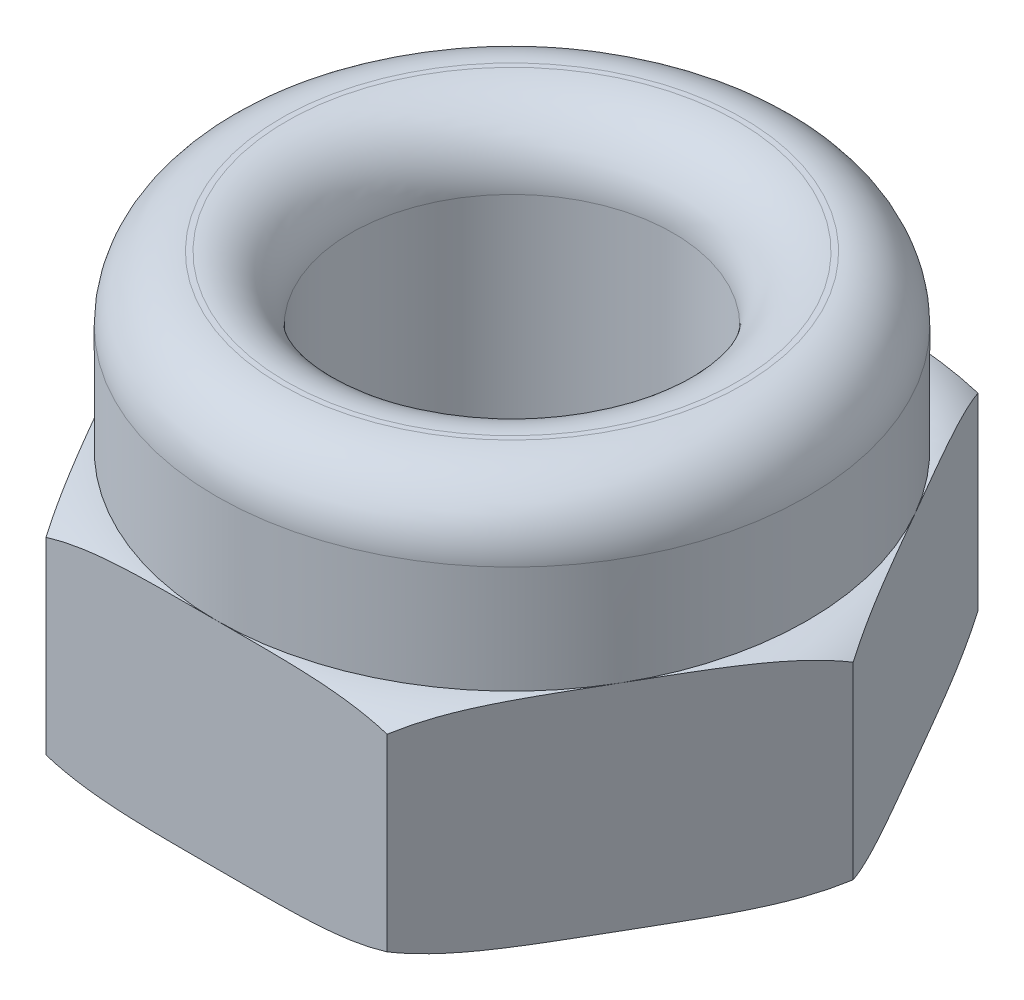
SolidWorks part; units mm, degrees
ref_plane "Front Plane" through (0, 0, 0) normal (0, 0, 1) x (1, 0, 0)
ref_plane "Top Plane" through (0, 0, 0) normal (0, 1, 0) x (1, 0, 0)
ref_plane "Right Plane" through (0, 0, 0) normal (1, 0, 0) x (0, 0, -1)
sketch "Sketch1" plane through (0, 0, 0) normal (0, 1, 0) x (1, 0, 0)
  line L1 (3.1754, 0) -> (1.5877, 2.75)
  line L2 (1.5877, 2.75) -> (-1.5877, 2.75)
  line L3 (-1.5877, 2.75) -> (-3.1754, 0)
  line L4 (-3.1754, 0) -> (-1.5877, -2.75)
  line L5 (-1.5877, -2.75) -> (1.5877, -2.75)
  line L6 (1.5877, -2.75) -> (3.1754, 0)
  circle A0 centre (0, 0) radius 2.75 construction
  circle A1 centre (0, 0) radius 1.5
  dimension "D1" = 3
  dimension "D2" = 5.5
extrude "Boss-Extrude1" add sketch "Sketch1" along normal mid plane 2
sketch "Sketch2" plane through (0, 0, 0) normal (0, 0, 1) x (1, 0, 0)
  line L1 (0, -1) -> (-3.1754, -1) construction
  line L2 (-1.5877, -1) -> (1.5877, -1) construction
  line L3 (-2.75, -1) -> (-2.75, 0) construction
  line L4 (-3.55, -0.2) -> (-3.55, -1)
  line L5 (-3.55, -1) -> (-2.75, -1)
  line L6 (0, 0) -> (0, 4.8499) construction
  arc A0 (-2.75, -1) -> (-3.55, -0.2) centre (-2.75, -0.2) cw
  dimension "D1" = 0.8
  dimension "D2" = 0.8
revolve "Cut-Revolve1" cut sketch "Sketch2" angle 360 about L6
mirror "Mirror2" about plane through (0, 0, 0) normal (0, 1, 0) of "Cut-Revolve1"
sketch "Sketch3" plane through (0, 1, 0) normal (0, 1, 0) x (1, 0, 0)
  circle A0 centre (0, 0) radius 1.5 construction
  circle A1 centre (0, 0) radius 1.5
  arc A6 (-2.3816, -1.375) -> (0, -2.75) centre (0, 0) ccw
  arc A7 (0, -2.75) -> (2.3816, -1.375) centre (0, 0) ccw
  arc A8 (2.3816, -1.375) -> (2.3816, 1.375) centre (0, 0) ccw
  arc A9 (2.3816, 1.375) -> (0, 2.75) centre (0, 0) ccw
  arc A10 (0, 2.75) -> (-2.3816, 1.375) centre (0, 0) ccw
  arc A11 (-2.3816, 1.375) -> (-2.3816, -1.375) centre (0, 0) ccw
  arc A12 (-2.3816, -1.375) -> (0, -2.75) centre (0, 0) ccw
  arc A13 (0, -2.75) -> (2.3816, -1.375) centre (0, 0) ccw
  arc A14 (2.3816, -1.375) -> (2.3816, 1.375) centre (0, 0) ccw
  arc A15 (2.3816, 1.375) -> (0, 2.75) centre (0, 0) ccw
  arc A16 (0, 2.75) -> (-2.3816, 1.375) centre (0, 0) ccw
  arc A17 (-2.3816, 1.375) -> (-2.3816, -1.375) centre (0, 0) ccw
  dimension "D1" = 0
extrude "Boss-Extrude2" add sketch "Sketch3" along normal blind 3.6 from surface at -2 starting at face at (0, -1, 1.5)
chamfer "Chamfer1" distance 0.2 angle 45 1 edges at (0, -1, 1.5)
fillet "Fillet1" radius 0.6 2 edges at (0, 2.6, 1.5) (0, 2.6, 2.75)
equation "\"D2@Sketch2\"=\"D1@Sketch2\""
